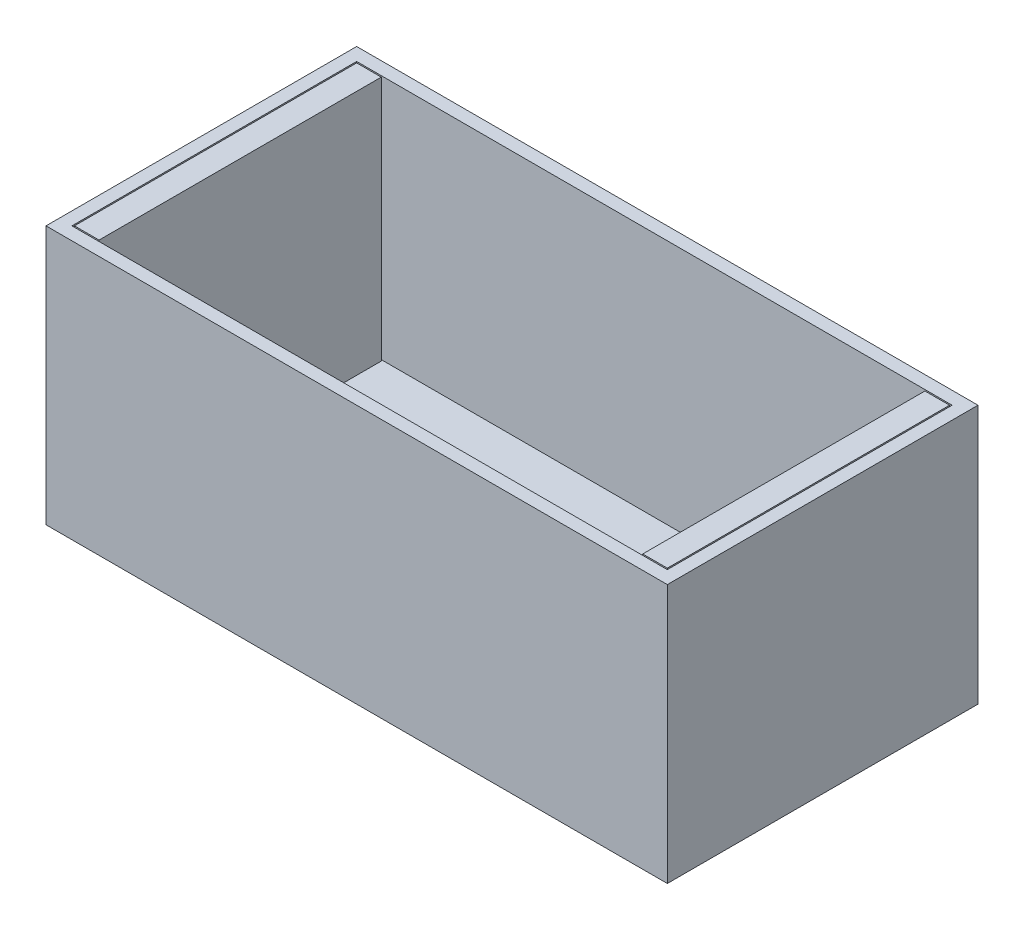
SolidWorks part; units mm, degrees
ref_plane "Front Plane" through (0, 0, 0) normal (0, 0, 1) x (1, 0, 0)
ref_plane "Top Plane" through (0, 0, 0) normal (0, 1, 0) x (1, 0, 0)
ref_plane "Right Plane" through (0, 0, 0) normal (1, 0, 0) x (0, 0, -1)
sketch "Sketch1" plane through (0, 0, 0) normal (0, 1, 0) x (1, 0, 0)
  line L1 (-304.8, -152.4) -> (304.8, -152.4)
  line L2 (-304.8, -152.4) -> (-304.8, 152.4)
  line L3 (-304.8, 152.4) -> (304.8, 152.4)
  line L4 (304.8, -152.4) -> (304.8, 152.4)
  line L5 (-304.8, -152.4) -> (304.8, 152.4) construction
  line L6 (-304.8, 152.4) -> (304.8, -152.4) construction
  point P0 (0, 0)
  dimension "D1" = 609.6
  dimension "D2" = 304.8
extrude "Boss-Extrude1" add sketch "Sketch1" along normal blind 254 contours L1 L4 L3 L2
shell "Shell1" thickness 12.7
sketch "Sketch2" plane through (0, 12.7, 0) normal (0, 1, 0) x (1, 0, 0)
  line L0 (-292.1, -139.7) -> (292.1, -139.7) construction
  line L1 (-290.83, 138.43) -> (-266.7, 138.43)
  line L2 (-290.83, 138.43) -> (-290.83, -138.43)
  line L3 (-290.83, -138.43) -> (-266.7, -138.43)
  line L4 (-266.7, 138.43) -> (-266.7, -138.43)
  line L5 (-292.1, 139.7) -> (292.1, 139.7) construction
  line L10 (-292.1, -139.7) -> (-292.1, 139.7) construction
  point P16 (0, 0)
  dimension "D1" = 24.13
  dimension "D3" = 1.27
  dimension "D4" = 1.27
  dimension "D5" = 1.27
extrude "Boss-Extrude3" add sketch "Sketch2" along normal blind 241.3
mirror "Mirror1" about plane through (0, 0, 0) normal (1, 0, 0) of "Boss-Extrude3"
